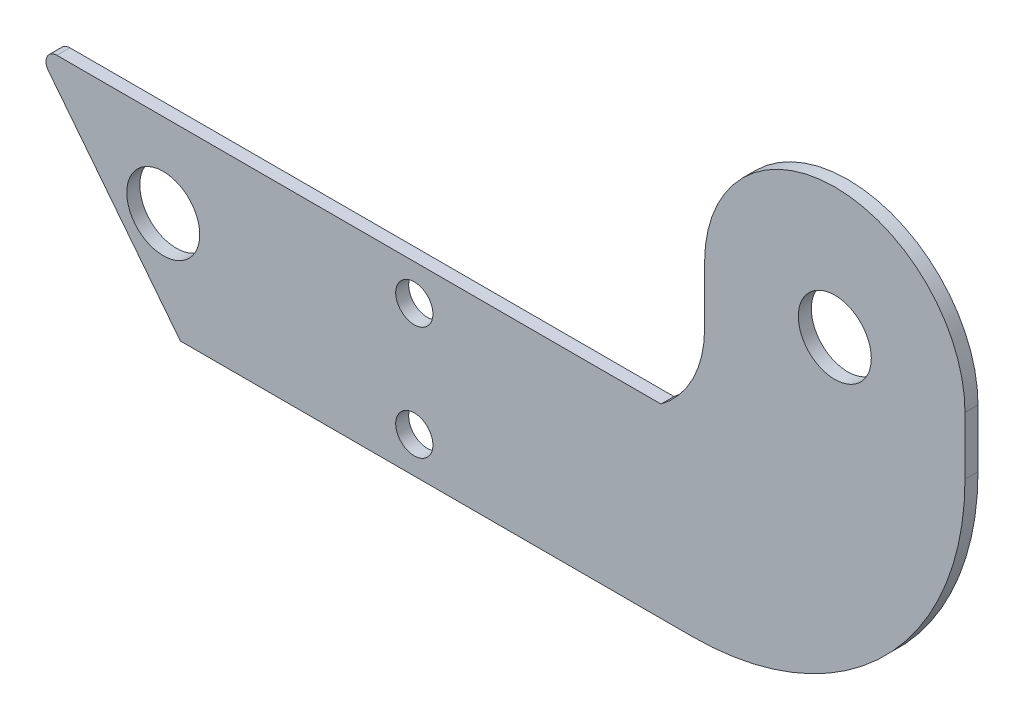
SolidWorks part; units mm, degrees
ref_plane "Plano frontal" through (0, 0, 0) normal (0, 0, 1) x (1, 0, 0)
ref_plane "Plano superior" through (0, 0, 0) normal (0, 1, 0) x (1, 0, 0)
ref_plane "Plano direito" through (0, 0, 0) normal (1, 0, 0) x (0, 0, -1)
sketch "Esboço1" plane through (0, 0, 0) normal (0, 0, 1) x (1, 0, 0)
  line L1 (-18.0186, 0) -> (-18.0186, -8)
  line L2 (-24.0556, -20.0277) -> (-110.7514, -20.0277)
  line L3 (-19.7146, -45.7332) -> (-90.5666, -45.7332)
  line L5 (-110.7514, -20.0277) -> (-90.5666, -45.7332)
  line L6 (18.0186, 0) -> (18.0186, -8)
  arc A0 (18.0186, 0) -> (-18.0186, 0) centre (0, 0) ccw
  arc A2 (-18.0186, -8) -> (-24.0556, -20.0277) centre (-33.0186, -8) cw
  circle A3 centre (0, 0) radius 5.05
  circle A4 centre (-58.1953, -25.0277) radius 2.5741
  circle A5 centre (-58.1953, -40.7332) radius 2.5741
  circle A6 centre (-92.938, -31.64) radius 5.05
  arc A7 (18.0186, -8) -> (-19.7146, -45.7332) centre (-19.7146, -8) cw
  dimension "D1" = 5
  dimension "D2" = 5
  dimension "D3" = 6.8387
extrude "Ressalto-extrusão1" add sketch "Esboço1" along normal blind 1.8
fillet "Filete1" radius 1.5 1 edges at (-110.7514, -20.0277, 0.9)
